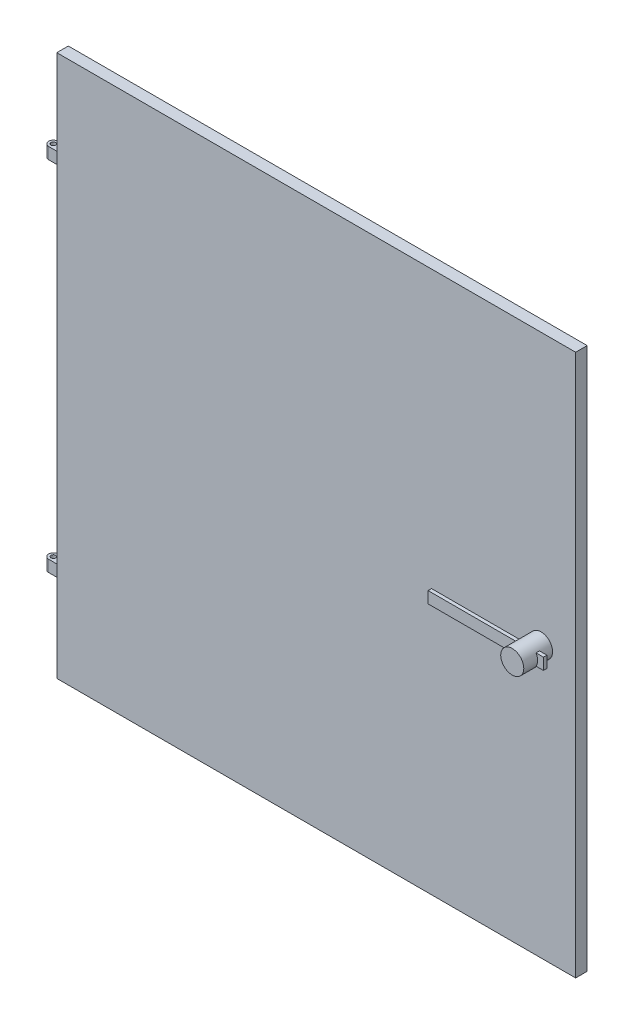
SolidWorks part; units mm, degrees
ref_plane "Front" through (0, 0, 0) normal (0, 0, 1) x (1, 0, 0)
ref_plane "Top" through (0, 0, 0) normal (0, 1, 0) x (1, 0, 0)
ref_plane "Right" through (0, 0, 0) normal (1, 0, 0) x (0, 0, -1)
other "Configuration Table"
sketch "Sketch1" plane through (0, 0, 0) normal (0, 0, 1) x (1, 0, 0)
  line L1 (0, 0) -> (450, 0)
  line L2 (0, 0) -> (0, 470)
  line L3 (0, 470) -> (450, 470)
  line L4 (450, 0) -> (450, 470)
  dimension "D1" = 450
  dimension "D2" = 470
extrude "Base-Extrude" add sketch "Sketch1" along normal blind 10
shell "Shell1" thickness 2
ref_plane "Plane4" through (0, 395, 0) normal (0, 1, 0) x (-1, 0, 0)
sketch "Sketch2" plane through (0, 395, 0) normal (0, 1, 0) x (-1, 0, 0)
  line L0 (8, 9) -> (0, 9)
  line L1 (0, 9) -> (0, 1)
  line L2 (0, 1) -> (8, 1)
  line L3 (0, 10) -> (0, 0) construction
  arc A0 (8, 1) -> (8, 9) centre (8, 5) ccw
  circle A1 centre (8, 5) radius 2
  point P5 (0, 5)
  dimension "D3" = 4
  dimension "D1" = 8
  dimension "D2" = 8
extrude "Boss-Extrude1" add sketch "Sketch2" against normal blind 10
ref_plane "Plane5" through (0, 235, 0) normal (0, 1, 0) x (-1, 0, 0)
mirror "Mirror1" about plane through (0, 235, 0) normal (0, 1, 0) of "Boss-Extrude1"
sketch "Sketch3" plane through (0, 0, 10) normal (0, 0, 1) x (1, 0, 0)
  line L0 (450, 235) -> (420, 235) construction
  line L1 (450, 0) -> (450, 470) construction
  circle A0 centre (420, 235) radius 10
  dimension "D2" = 20
  dimension "D1" = 30
extrude "Boss-Extrude2" add sketch "Sketch3" along normal blind 25
ref_plane "Plane6" through (0, 0, 20) normal (0, 0, 1) x (1, 0, 0)
sketch "Sketch4" plane through (0, 0, 20) normal (0, 0, 1) x (1, 0, 0)
  line L0 (450, 235) -> (253.3258, 235) construction
  line L1 (450, 0) -> (450, 470) construction
  line L4 (335, 230) -> (435, 230)
  line L5 (335, 230) -> (335, 240)
  line L6 (335, 240) -> (435, 240)
  line L7 (435, 230) -> (435, 240)
  circle A1 centre (420, 235) radius 10 construction
  dimension "D3" = 15
  dimension "D1" = 10
  dimension "D2" = 100
extrude "Boss-Extrude3" add sketch "Sketch4" along normal blind 3
